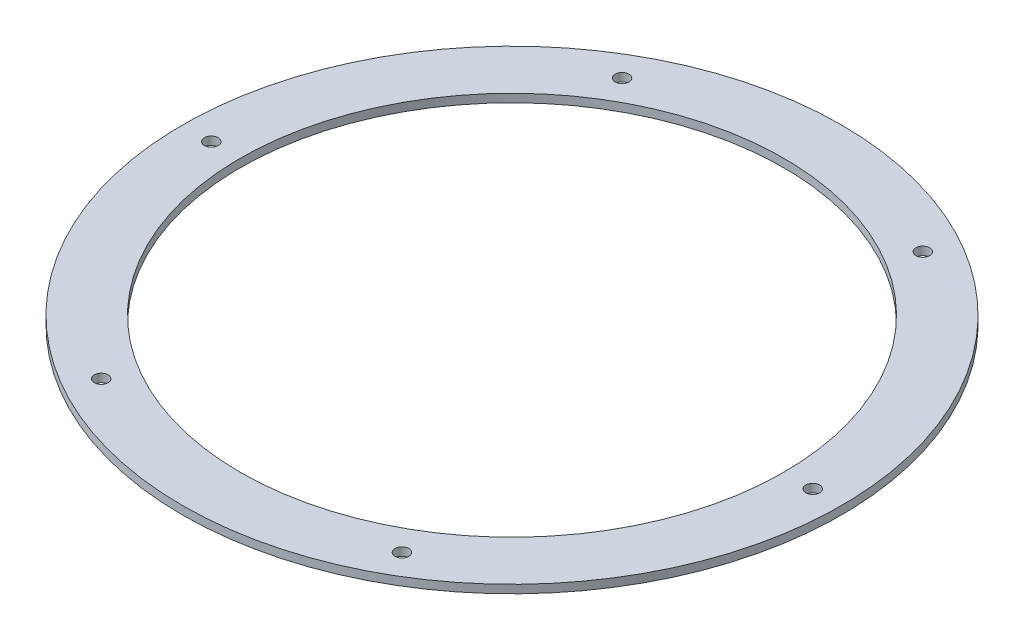
SolidWorks part; units mm, degrees
ref_plane "Front Plane" through (0, 0, 0) normal (0, 0, 1) x (1, 0, 0)
ref_plane "Top Plane" through (0, 0, 0) normal (0, 1, 0) x (1, 0, 0)
ref_plane "Right Plane" through (0, 0, 0) normal (1, 0, 0) x (0, 0, -1)
sketch "Sketch1" plane through (0, 0, 0) normal (0, 1, 0) x (1, 0, 0)
  line L0 (-120, 0) -> (-99, 0) construction
  circle A0 centre (0, 0) radius 99
  circle A1 centre (0, 0) radius 120
  circle A2 centre (-109.5, 0) radius 2.5
  circle A3 centre (-54.75, 94.8298) radius 2.5
  circle A4 centre (54.75, 94.8298) radius 2.5
  circle A5 centre (109.5, 0) radius 2.5
  circle A6 centre (54.75, -94.8298) radius 2.5
  circle A7 centre (-54.75, -94.8298) radius 2.5
  point P21 (0, 0)
  dimension "D1" = 198
  dimension "D2" = 240
  dimension "D3" = 5
  dimension "D4" = 6
extrude "Boss-Extrude1" add sketch "Sketch1" along normal blind 3
